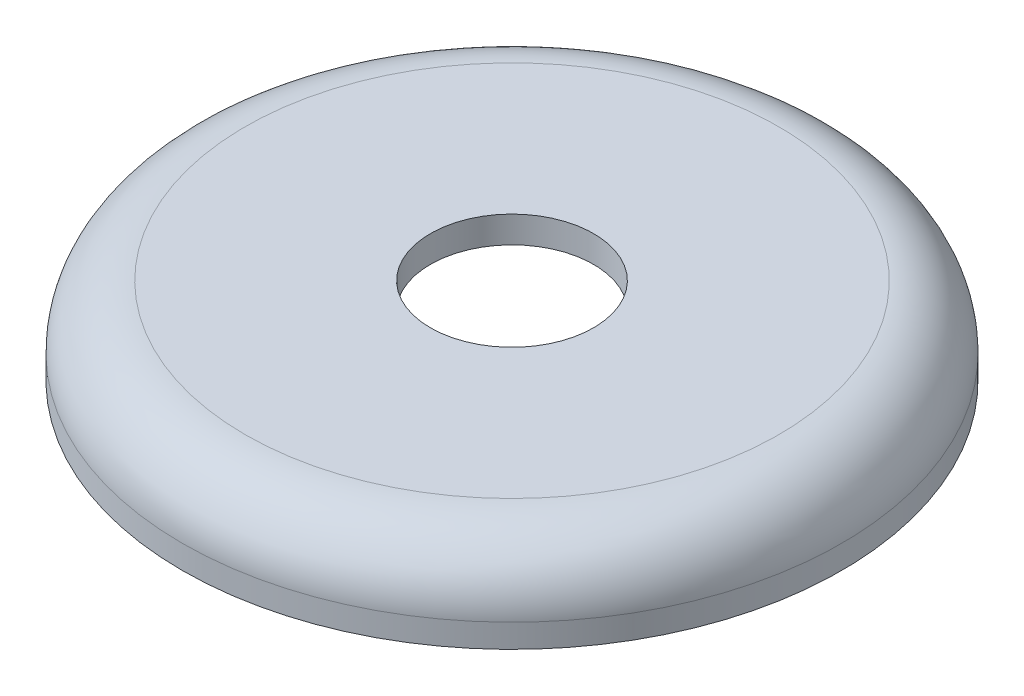
SolidWorks part; units mm, degrees
ref_plane "Front Plane" through (0, 0, 0) normal (0, 0, 1) x (1, 0, 0)
ref_plane "Top Plane" through (0, 0, 0) normal (0, 1, 0) x (1, 0, 0)
ref_plane "Right Plane" through (0, 0, 0) normal (1, 0, 0) x (0, 0, -1)
sketch "Sketch1" plane through (0, 0, 0) normal (0, 1, 0) x (1, 0, 0)
  circle A0 centre (0, 0) radius 21
  dimension "D1" = 42
extrude "Boss-Extrude1" add sketch "Sketch1" along normal blind 5.5
fillet "Fillet2" radius 4 1 edges at (0, 5.5, 21)
shell "Shell3" thickness 1.7
sketch "Sketch3" plane through (0, 5.5, 0) normal (0, 1, 0) x (1, 0, 0)
  circle A0 centre (0, 0) radius 5.2
  dimension "D1" = 10.4
extrude "Cut-Extrude2" cut sketch "Sketch3" against normal through all contours A0
